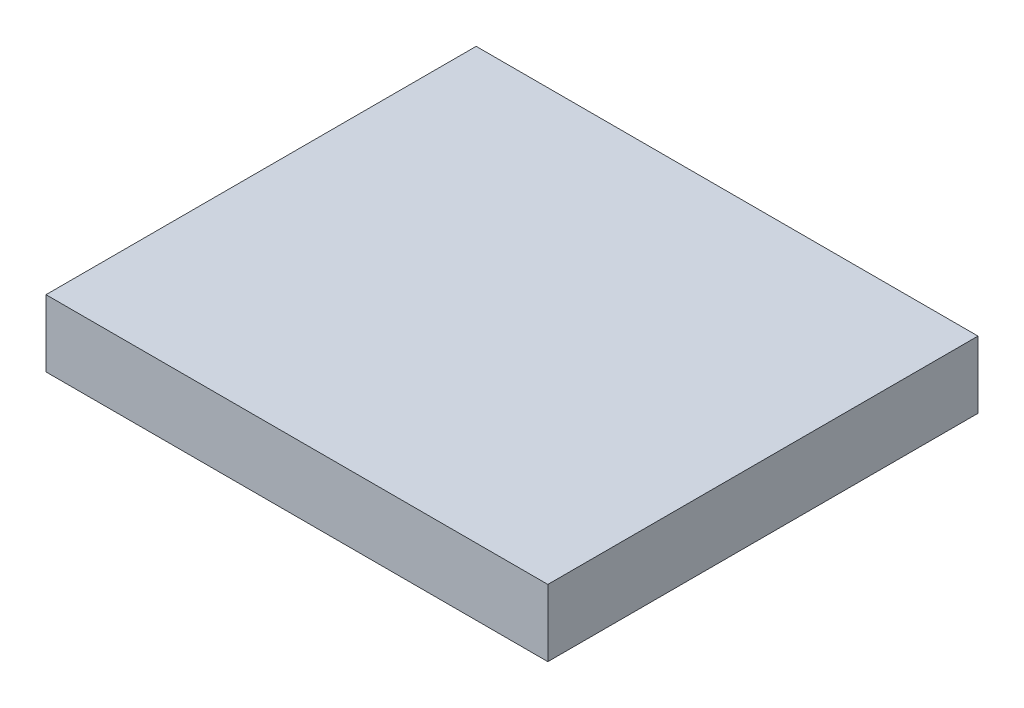
SolidWorks part; units mm, degrees
ref_plane "Front Plane" through (0, 0, 0) normal (0, 0, 1) x (1, 0, 0)
ref_plane "Top Plane" through (0, 0, 0) normal (0, 1, 0) x (1, 0, 0)
ref_plane "Right Plane" through (0, 0, 0) normal (1, 0, 0) x (0, 0, -1)
sketch "Sketch1" plane through (0, 0, 0) normal (0, 1, 0) x (1, 0, 0)
  line L1 (0, 0) -> (21, 0)
  line L2 (0, 0) -> (0, 18)
  line L3 (0, 18) -> (21, 18)
  line L4 (21, 0) -> (21, 18)
  dimension "D1" = 21
  dimension "D2" = 18
extrude "Boss-Extrude1" add sketch "Sketch1" along normal blind 2.8
